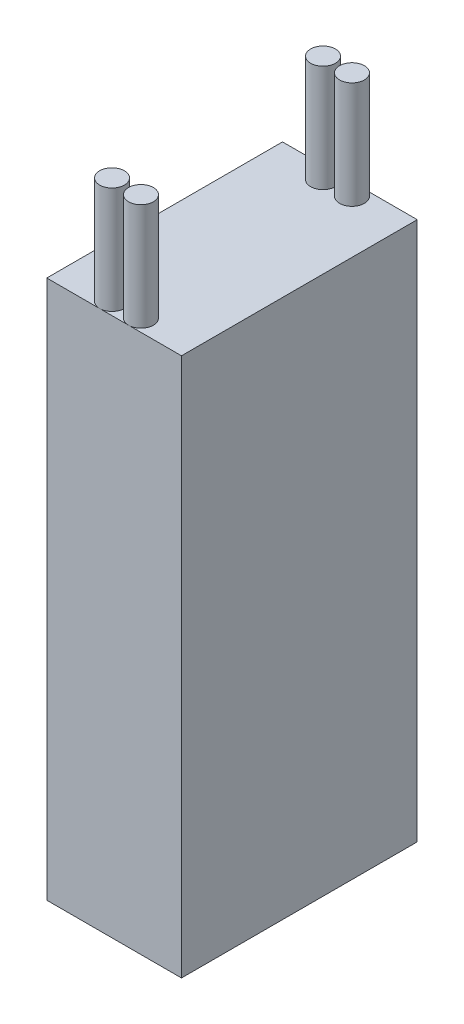
SolidWorks part; units mm, degrees
ref_plane "Front Plane" through (0, 0, 0) normal (0, 0, 1) x (1, 0, 0)
ref_plane "Top Plane" through (0, 0, 0) normal (0, 1, 0) x (1, 0, 0)
ref_plane "Right Plane" through (0, 0, 0) normal (1, 0, 0) x (0, 0, -1)
sketch "Sketch1" plane through (0, 0, 0) normal (0, 1, 0) x (1, 0, 0)
  line L1 (0, 0) -> (16, 0)
  line L2 (0, 0) -> (0, 28)
  line L3 (0, 28) -> (16, 28)
  line L4 (16, 0) -> (16, 28)
  dimension "D1" = 16
  dimension "D2" = 28
extrude "Boss-Extrude1" add sketch "Sketch1" along normal blind 64
sketch "Sketch2" plane through (0, 64, 0) normal (0, 1, 0) x (1, 0, 0)
  line L0 (8, 0) -> (8, 28.5935) construction
  line L5 (0, 14) -> (18.8062, 14) construction
  circle A0 centre (6.2801, 26.5301) radius 1.4699
  circle A1 centre (9.7199, 26.5301) radius 1.4699
  circle A2 centre (6.2801, 1.4699) radius 1.4699
  circle A3 centre (9.7199, 1.4699) radius 1.4699
  dimension "D1" = 3.4399
  dimension "D2" = 1.7199
extrude "Boss-Extrude8" add sketch "Sketch2" along normal blind 12.7
